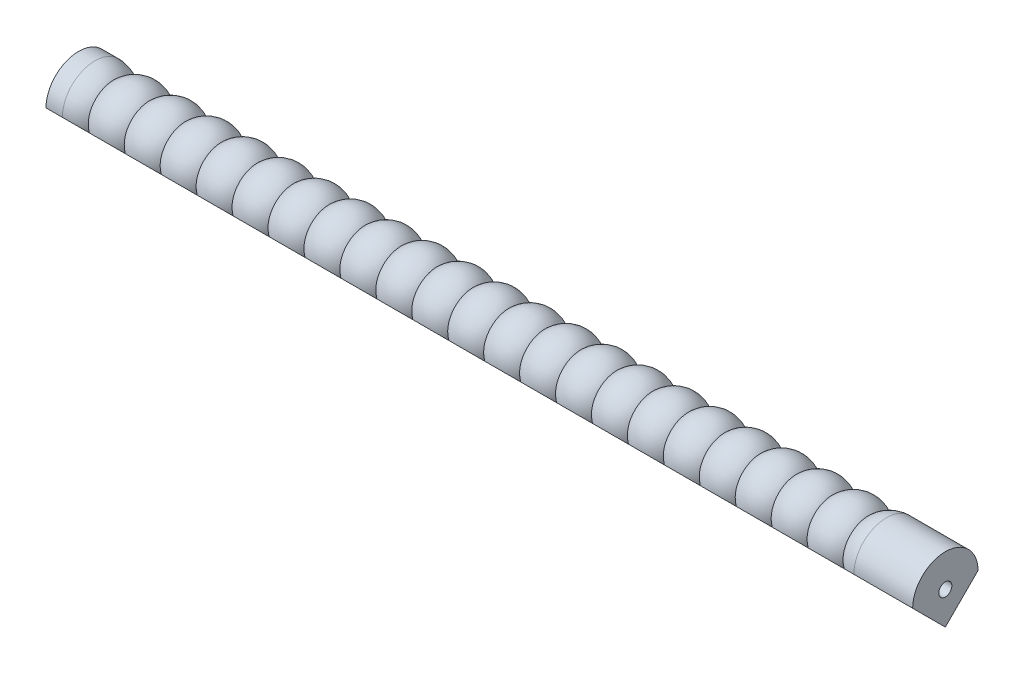
SolidWorks part; units mm, degrees
ref_plane "Front Plane" through (0, 0, 0) normal (0, 0, 1) x (1, 0, 0)
ref_plane "Top Plane" through (0, 0, 0) normal (0, 1, 0) x (1, 0, 0)
ref_plane "Right Plane" through (0, 0, 0) normal (1, 0, 0) x (0, 0, -1)
sketch "Sketch1" plane through (0, 0, 0) normal (0, 1, 0) x (1, 0, 0)
  line L0 (0, 0) -> (0, 5)
  line L1 (0, 0) -> (2.5, 0)
  line L2 (2.5, 0) -> (2.5, 2.5)
  line L4 (9.5, 1) -> (10.875, 1)
  line L5 (10.875, 1) -> (10.875, 3.9047) construction
  line L6 (0, 5) -> (2.5, 5)
  line L7 (5.375, 3.9047) -> (5.375, 1) construction
  line L8 (4, 1) -> (5.375, 1)
  line L9 (5.375, 1) -> (6.75, 1)
  line L10 (4, 1) -> (4, -0.5373) construction
  line L11 (10.875, 1) -> (12.25, 1)
  line L12 (15, 1) -> (16.375, 1)
  line L13 (16.375, 1) -> (17.75, 1)
  line L14 (20.5, 1) -> (21.875, 1)
  line L15 (21.875, 1) -> (23.25, 1)
  line L16 (26, 1) -> (27.375, 1)
  line L17 (27.375, 1) -> (28.75, 1)
  line L18 (31.5, 1) -> (32.875, 1)
  line L19 (32.875, 1) -> (34.25, 1)
  line L20 (37, 1) -> (38.375, 1)
  line L21 (38.375, 1) -> (39.75, 1)
  line L22 (42.5, 1) -> (43.875, 1)
  line L23 (43.875, 1) -> (45.25, 1)
  line L24 (48, 1) -> (49.375, 1)
  line L25 (49.375, 1) -> (50.75, 1)
  line L26 (53.5, 1) -> (54.875, 1)
  line L27 (54.875, 1) -> (56.25, 1)
  line L28 (59, 1) -> (60.375, 1)
  line L29 (60.375, 1) -> (61.75, 1)
  line L30 (64.5, 1) -> (65.875, 1)
  line L31 (65.875, 1) -> (67.25, 1)
  line L32 (70, 1) -> (71.375, 1)
  line L33 (71.375, 1) -> (72.75, 1)
  line L34 (75.5, 1) -> (76.875, 1)
  line L35 (76.875, 1) -> (78.25, 1)
  line L36 (81, 1) -> (82.375, 1)
  line L37 (82.375, 1) -> (83.75, 1)
  line L38 (86.5, 1) -> (87.875, 1)
  line L39 (87.875, 1) -> (89.25, 1)
  line L40 (92, 1) -> (93.375, 1)
  line L41 (93.375, 1) -> (94.75, 1)
  line L42 (97.5, 1) -> (98.875, 1)
  line L43 (98.875, 1) -> (100.25, 1)
  line L44 (103, 1) -> (104.375, 1)
  line L45 (104.375, 1) -> (105.75, 1)
  line L46 (108.5, 1) -> (109.875, 1)
  line L47 (109.875, 1) -> (111.25, 1)
  line L48 (114, 1) -> (115.375, 1)
  line L49 (115.375, 1) -> (116.75, 1)
  line L50 (119.5, 1) -> (120.875, 1)
  line L51 (5.375, 3.9047) -> (10.875, 3.9047) construction
  line L52 (120.875, 1) -> (122.25, 1)
  line L53 (123.625, 1) -> (123.625, 2.375) construction
  line L54 (123.625, 2.375) -> (123.625, 1) construction
  line L55 (125, 1) -> (132.625, 1)
  line L56 (132.625, 1) -> (132.625, 5)
  line L57 (132.625, 5) -> (123.625, 5)
  line L58 (123.625, 1) -> (125, 1) construction
  arc A2 (2.5, 2.5) -> (4, 1) centre (2.5, 1) cw
  arc A3 (6.75, 1) -> (9.5, 1) centre (8.125, 1) cw
  arc A4 (2.5, 5) -> (5.375, 3.9047) centre (2.5, 0.679) cw
  arc A5 (5.375, 3.9047) -> (10.875, 3.9047) centre (8.125, 1) cw
  arc A6 (10.875, 3.9047) -> (16.375, 3.9047) centre (13.625, 1) cw
  arc A7 (12.25, 1) -> (15, 1) centre (13.625, 1) cw
  arc A8 (16.375, 3.9047) -> (21.875, 3.9047) centre (19.125, 1) cw
  arc A9 (17.75, 1) -> (20.5, 1) centre (19.125, 1) cw
  arc A10 (21.875, 3.9047) -> (27.375, 3.9047) centre (24.625, 1) cw
  arc A11 (23.25, 1) -> (26, 1) centre (24.625, 1) cw
  arc A12 (27.375, 3.9047) -> (32.875, 3.9047) centre (30.125, 1) cw
  arc A13 (28.75, 1) -> (31.5, 1) centre (30.125, 1) cw
  arc A14 (32.875, 3.9047) -> (38.375, 3.9047) centre (35.625, 1) cw
  arc A15 (34.25, 1) -> (37, 1) centre (35.625, 1) cw
  arc A16 (38.375, 3.9047) -> (43.875, 3.9047) centre (41.125, 1) cw
  arc A17 (39.75, 1) -> (42.5, 1) centre (41.125, 1) cw
  arc A18 (43.875, 3.9047) -> (49.375, 3.9047) centre (46.625, 1) cw
  arc A19 (45.25, 1) -> (48, 1) centre (46.625, 1) cw
  arc A20 (49.375, 3.9047) -> (54.875, 3.9047) centre (52.125, 1) cw
  arc A21 (50.75, 1) -> (53.5, 1) centre (52.125, 1) cw
  arc A22 (54.875, 3.9047) -> (60.375, 3.9047) centre (57.625, 1) cw
  arc A23 (56.25, 1) -> (59, 1) centre (57.625, 1) cw
  arc A24 (60.375, 3.9047) -> (65.875, 3.9047) centre (63.125, 1) cw
  arc A25 (61.75, 1) -> (64.5, 1) centre (63.125, 1) cw
  arc A26 (65.875, 3.9047) -> (71.375, 3.9047) centre (68.625, 1) cw
  arc A27 (67.25, 1) -> (70, 1) centre (68.625, 1) cw
  arc A28 (71.375, 3.9047) -> (76.875, 3.9047) centre (74.125, 1) cw
  arc A29 (72.75, 1) -> (75.5, 1) centre (74.125, 1) cw
  arc A30 (76.875, 3.9047) -> (82.375, 3.9047) centre (79.625, 1) cw
  arc A31 (78.25, 1) -> (81, 1) centre (79.625, 1) cw
  arc A32 (82.375, 3.9047) -> (87.875, 3.9047) centre (85.125, 1) cw
  arc A33 (83.75, 1) -> (86.5, 1) centre (85.125, 1) cw
  arc A34 (87.875, 3.9047) -> (93.375, 3.9047) centre (90.625, 1) cw
  arc A35 (89.25, 1) -> (92, 1) centre (90.625, 1) cw
  arc A36 (93.375, 3.9047) -> (98.875, 3.9047) centre (96.125, 1) cw
  arc A37 (94.75, 1) -> (97.5, 1) centre (96.125, 1) cw
  arc A38 (98.875, 3.9047) -> (104.375, 3.9047) centre (101.625, 1) cw
  arc A39 (100.25, 1) -> (103, 1) centre (101.625, 1) cw
  arc A40 (104.375, 3.9047) -> (109.875, 3.9047) centre (107.125, 1) cw
  arc A41 (105.75, 1) -> (108.5, 1) centre (107.125, 1) cw
  arc A42 (109.875, 3.9047) -> (115.375, 3.9047) centre (112.625, 1) cw
  arc A43 (111.25, 1) -> (114, 1) centre (112.625, 1) cw
  arc A44 (115.375, 3.9047) -> (120.875, 3.9047) centre (118.125, 1) cw
  arc A45 (116.75, 1) -> (119.5, 1) centre (118.125, 1) cw
  arc A46 (122.25, 1) -> (125, 1) centre (123.625, 1) cw
  arc A47 (120.875, 3.9047) -> (123.625, 5) centre (123.625, 1) cw
  dimension "D9" = 21
  dimension "D8" = 5.5
  dimension "D1" = 5
  dimension "D2" = 2.5
  dimension "D3" = 2.5
  dimension "D4" = 4
  dimension "D5" = 2.75
  dimension "D6" = 1.375
  dimension "D7" = 5.5
  dimension "D10" = 2.5
  dimension "D11" = 5.5
  dimension "D12" = 1.375
  dimension "D13" = 1.375
  dimension "D14" = 9
  dimension "D15" = 4
  dimension "D16" = 9
revolve "Revolve2" add sketch "Sketch1" angle 360 about L1
sketch "Sketch2" plane through (0, 0, 0) normal (-1, 0, 0) x (0, 0, 1)
  line L0 (0, 0) -> (-5, 0)
  line L1 (0, 0) -> (5, 0)
  line L2 (0, -5) -> (-5, 0)
  line L3 (0, -5) -> (5, 0)
  circle A0 centre (0, 0) radius 5
  circle M6 centre (0, 0) radius 5
  dimension "D1" = 10
extrude "Cut-Extrude1" cut sketch "Sketch2" against normal blind 150 contours L3 M6 | L2 M6
